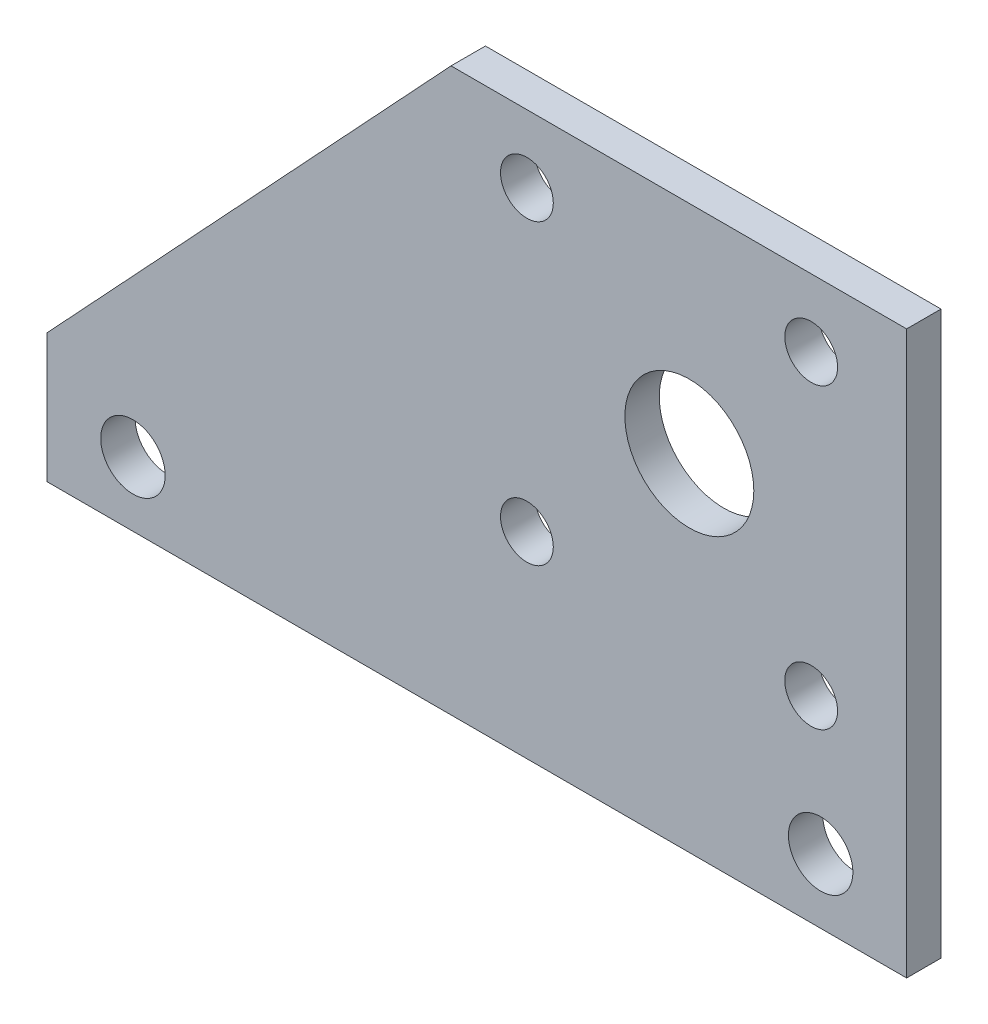
SolidWorks part; units mm, degrees
material "1023 Carbon Steel Sheet (SS)"
ref_plane "Front Plane" through (0, 0, 0) normal (0, 0, 1) x (1, 0, 0)
ref_plane "Top Plane" through (0, 0, 0) normal (0, 1, 0) x (1, 0, 0)
ref_plane "Right Plane" through (0, 0, 0) normal (1, 0, 0) x (0, 0, -1)
sketch "Sketch1" plane through (0, 0, 0) normal (0, 0, 1) x (1, 0, 0)
  line L0 (-6.35, 9.525) -> (23.4961, 41.525) construction
  line L1 (23.4961, 41.525) -> (57.15, 41.525) construction
  line L2 (57.15, 41.525) -> (57.15, 0) construction
  line L3 (57.15, 0) -> (44.45, 0) construction
  line L4 (15.1, 9.525) -> (64.1, 9.525)
  line L5 (64.1, 9.525) -> (64.1, 41.025)
  line L6 (64.1, 41.025) -> (15.1, 41.025)
  line L7 (15.1, 41.025) -> (15.1, 9.525)
  line L8 (15.1, 9.525) -> (64.1, 9.525)
  line L9 (64.1, 9.525) -> (64.1, 41.025)
  line L10 (64.1, 41.025) -> (15.1, 41.025)
  line L11 (15.1, 41.025) -> (15.1, 9.525)
  line L12 (44.45, 0) -> (6.35, 0) construction
  line L13 (6.35, 0) -> (-6.35, 0) construction
  line L14 (-6.35, 0) -> (-6.35, 9.525) construction
  line L15 (-6.35, 9.525) -> (23.4961, 41.525)
  line L16 (23.4961, 41.525) -> (57.15, 41.525)
  line L17 (57.15, 41.525) -> (57.15, 0)
  line L18 (57.15, 0) -> (44.45, 0)
  line L19 (44.45, 0) -> (6.35, 0)
  line L20 (6.35, 0) -> (-6.35, 0)
  line L21 (-6.35, 0) -> (-6.35, 9.525)
  circle A0 centre (0, 4.7625) radius 2.3812 construction
  circle A1 centre (50.8, 4.7625) radius 2.3812 construction
  circle A2 centre (0, 4.7625) radius 2.3812
  circle A3 centre (50.8, 4.7625) radius 2.3812
  dimension "D1" = 0
extrude "Boss-Extrude1" add sketch "Sketch1" along normal blind 2.54 contours L15 L16 L17 L18 L19 L20 L21 | A2 | A3
sketch "Sketch2" plane through (0, 0, 2.54) normal (0, 0, 1) x (1, 0, 0)
  line L1 (29.1, 36.525) -> (50.1, 36.525) construction
  line L2 (29.1, 36.525) -> (29.1, 14.525) construction
  line L3 (29.1, 14.525) -> (50.1, 14.525) construction
  line L4 (50.1, 36.525) -> (50.1, 14.525) construction
  line L5 (29.1, 36.525) -> (50.1, 14.525) construction
  line L6 (29.1, 14.525) -> (50.1, 36.525) construction
  circle A0 centre (39.6, 25.525) radius 5 construction
  circle A1 centre (39.6, 25.525) radius 5 construction
  dimension "D1" = 21
  dimension "D2" = 22
hole_wizard "M3.5 Clearance Hole1" positions "Sketch4" profile "Sketch3" hole size "M3.5" standard "ANSI Metric"
sketch "Sketch4" plane through (0, 0, 2.54) normal (0, 0, 1) x (1, 0, 0)
  point P0 (29.1, 36.525)
  point P3 (50.1, 36.525)
  point P6 (50.1, 14.525)
  point P9 (29.1, 14.525)
sketch "Sketch3" plane through (29.1, 36.525, 2.54) normal (1, 0, 0) x (0, -1, 0)
  line L0 (0, 0) -> (0, 13.8717)
  line L1 (0, 13.8717) -> (1.95, 12.7)
  line L2 (1.95, 12.7) -> (1.95, 0)
  line L5 (1.95, 0) -> (0, 0)
  line L10 (0, 13.8717) -> (-1.95, 12.7) construction
  line L11 (0, -6.35) -> (0, 107.95) construction
  dimension "Hole Dia." = 3.9
  dimension "Hole Depth" = 12.7
  dimension "Drill Angle" = 118
sketch "Sketch5" plane through (0, 0, 2.54) normal (0, 0, 1) x (1, 0, 0)
  line L1 (50.1, 36.525) -> (50.1, 14.525) construction
  circle A0 centre (41.1, 25.525) radius 4.7625
  dimension "D1" = 9
  dimension "D2" = 9.525
extrude "Cut-Extrude1" cut sketch "Sketch5" against normal through all
